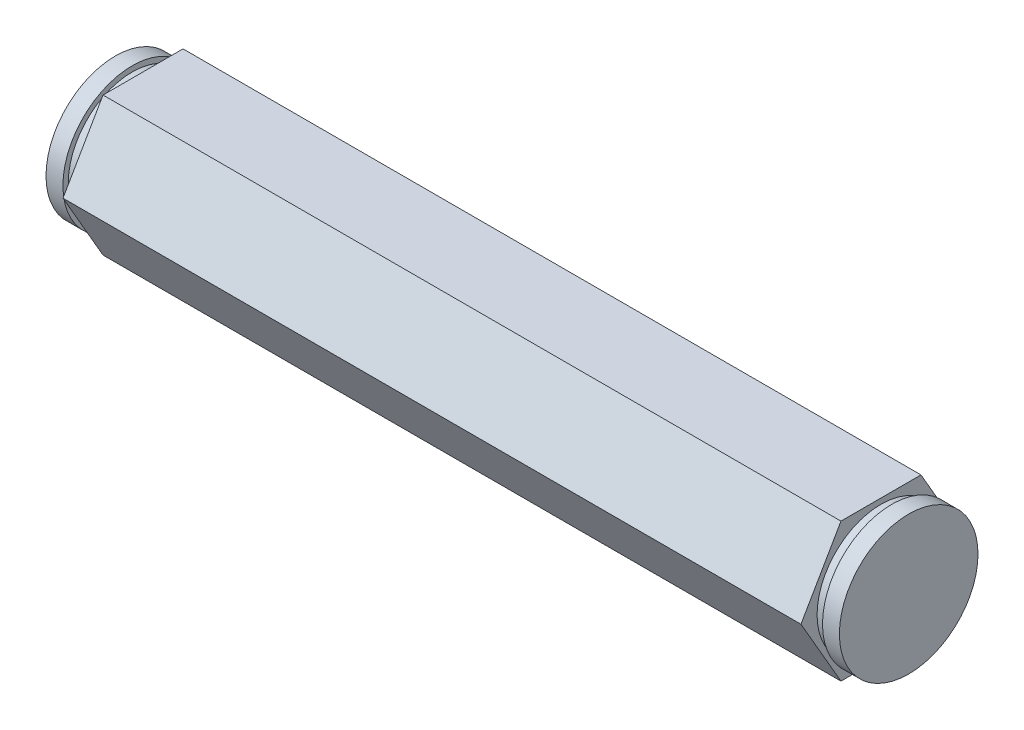
SolidWorks part; units mm, degrees
material "7075-T6 (SN)"
ref_plane "Front Plane" through (0, 0, 0) normal (0, 0, 1) x (1, 0, 0)
ref_plane "Top Plane" through (0, 0, 0) normal (0, 1, 0) x (1, 0, 0)
ref_plane "Right Plane" through (0, 0, 0) normal (1, 0, 0) x (0, 0, -1)
sketch "Sketch1" plane through (0, 0, 0) normal (1, 0, 0) x (0, 0, -1)
  line L1 (7.3323, 0) -> (3.6662, 6.35)
  line L2 (3.6662, 6.35) -> (-3.6662, 6.35)
  line L3 (-3.6662, 6.35) -> (-7.3323, 0)
  line L4 (-7.3323, 0) -> (-3.6662, -6.35)
  line L5 (-3.6662, -6.35) -> (3.6662, -6.35)
  line L6 (3.6662, -6.35) -> (7.3323, 0)
  circle A0 centre (0, 0) radius 6.35 construction
  dimension "D1" = 12.7
extrude "Boss-Extrude1" add sketch "Sketch1" along normal mid plane 72.6975
sketch "Sketch2" plane through (0, 0, 0) normal (0, 1, 0) x (1, 0, 0)
  line L0 (33.8088, -5.8547) -> (34.7994, -5.8547)
  line L1 (34.7994, -5.8547) -> (34.7994, -6.35)
  line L2 (34.7994, -6.35) -> (36.3488, -6.35)
  line L3 (36.3488, -6.35) -> (36.3488, -8.89)
  line L4 (36.3488, -8.89) -> (33.8088, -8.89)
  line L5 (33.8088, -8.89) -> (33.8088, -5.8547)
  line L6 (0, 0) -> (49.5443, 0) construction
  dimension "D1" = 2.54
  dimension "D2" = 6.35
  dimension "D3" = 5.8547
  dimension "D4" = 2.54
  dimension "D5" = 0.9906
revolve "Cut-Revolve1" cut sketch "Sketch2" angle 360 about L6
mirror "Mirror1" about plane through (0, 0, 0) normal (1, 0, 0) of "Cut-Revolve1"
